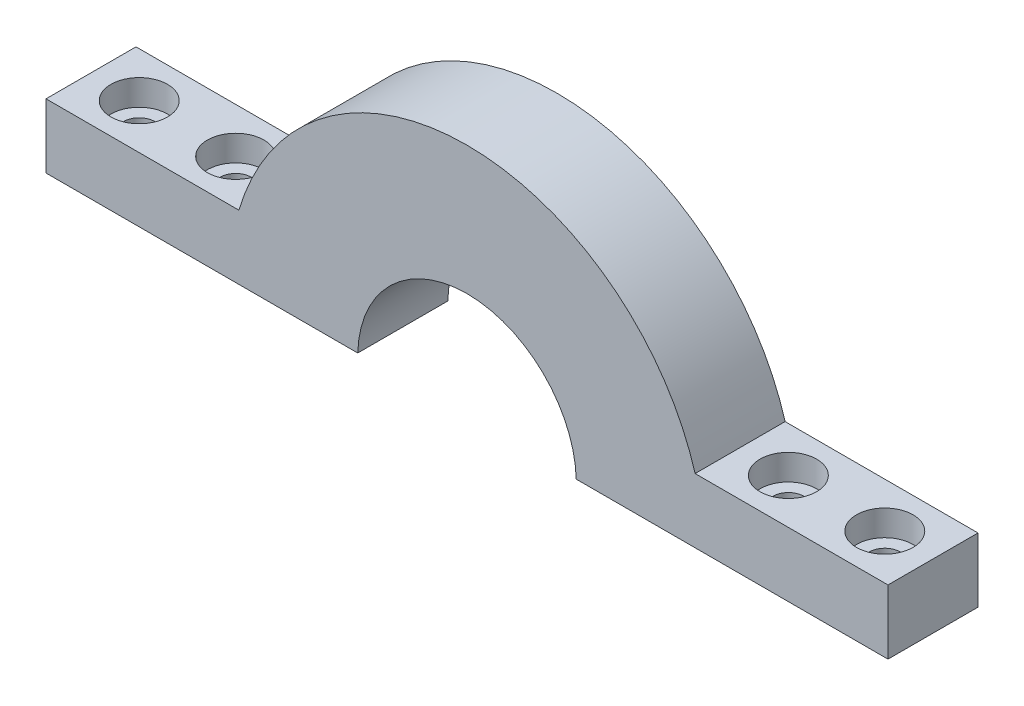
SolidWorks part; units mm, degrees
ref_plane "Front Plane" through (0, 0, 0) normal (0, 0, 1) x (1, 0, 0)
ref_plane "Top Plane" through (0, 0, 0) normal (0, 1, 0) x (1, 0, 0)
ref_plane "Right Plane" through (0, 0, 0) normal (1, 0, 0) x (0, 0, -1)
sketch "Sketch1" plane through (0, 0, 0) normal (0, 0, 1) x (1, 0, 0)
  line L0 (-18.4983, 0.25) -> (-32.7394, 0.25)
  line L1 (-32.7394, 0.25) -> (-32.7394, 5.25)
  line L2 (-32.7394, 5.25) -> (-17.7394, 5.25)
  line L3 (18.4983, 0.25) -> (32.7394, 0.25)
  line L4 (32.7394, 0.25) -> (32.7394, 5.25)
  line L5 (32.7394, 5.25) -> (17.7394, 5.25)
  line L6 (-18.4983, 0.25) -> (-8.4963, 0.25)
  line L7 (18.4983, 0.25) -> (8.4963, 0.25)
  arc A0 (8.4963, 0.25) -> (-8.4963, 0.25) centre (0, 0) ccw
  arc A3 (17.7394, 5.25) -> (-17.7394, 5.25) centre (0, 0) ccw
  dimension "D2" = 17
  dimension "D3" = 0.25
  dimension "D1" = 10
  dimension "D4" = 5
  dimension "D5" = 15
extrude "Boss-Extrude1" add sketch "Sketch1" against normal blind 7
sketch "Sketch2" plane through (0, 5.25, 0) normal (0, 1, 0) x (1, 0, 0)
  line L0 (-32.7394, 3.5) -> (32.7394, 3.5) construction
  line L1 (-32.7394, 7) -> (-32.7394, 0) construction
  line L2 (32.7394, 7) -> (32.7394, 0) construction
  line L3 (-25.2394, 7) -> (-25.2394, 0) construction
  line L4 (-17.7394, 7) -> (-32.7394, 7) construction
  line L5 (-17.7394, 0) -> (-32.7394, 0) construction
  line L6 (-28.9894, 7) -> (-28.9894, 0) construction
  line L7 (-21.4894, 7) -> (-21.4894, 0) construction
  line L8 (25.2394, 7) -> (25.2394, 0) construction
  line L9 (32.7394, 7) -> (17.7394, 7) construction
  line L10 (32.7394, 0) -> (17.7394, 0) construction
  line L11 (28.9894, 7) -> (28.9894, 0) construction
  line L12 (21.4894, 7) -> (21.4894, 0) construction
  point P26 (-28.9894, 3.5)
  point P27 (-21.4894, 3.5)
  point P28 (21.4894, 3.5)
  point P29 (28.9894, 3.5)
  dimension "D1" = 3.75
  dimension "D2" = 3.75
  dimension "D3" = 3.75
  dimension "D4" = 3.75
hole_wizard "CBORE for M2 SHCS1" positions "Sketch2" profile "Sketch3" counterbore size "M2" standard "ANSI Metric" end condition through all
sketch "Sketch3" plane through (28.9894, 5.25, -3.5) normal (1, 0, 0) x (0, 0, 1)
  line L0 (0, 0) -> (0, 5)
  line L1 (0, 5) -> (1.2, 5)
  line L3 (1.2, 5) -> (1.2, 2)
  line L4 (1.2, 2) -> (2.2, 2)
  line L5 (2.2, 2) -> (2.2, 0)
  line L7 (2.2, 0) -> (0, 0)
  line L11 (0, -6.35) -> (0, 107.95) construction
  dimension "Thru Hole Dia." = 2.4
  dimension "Thru Hole Depth" = 5
  dimension "C'Bore Dia." = 4.4
  dimension "C'Bore Depth" = 2
